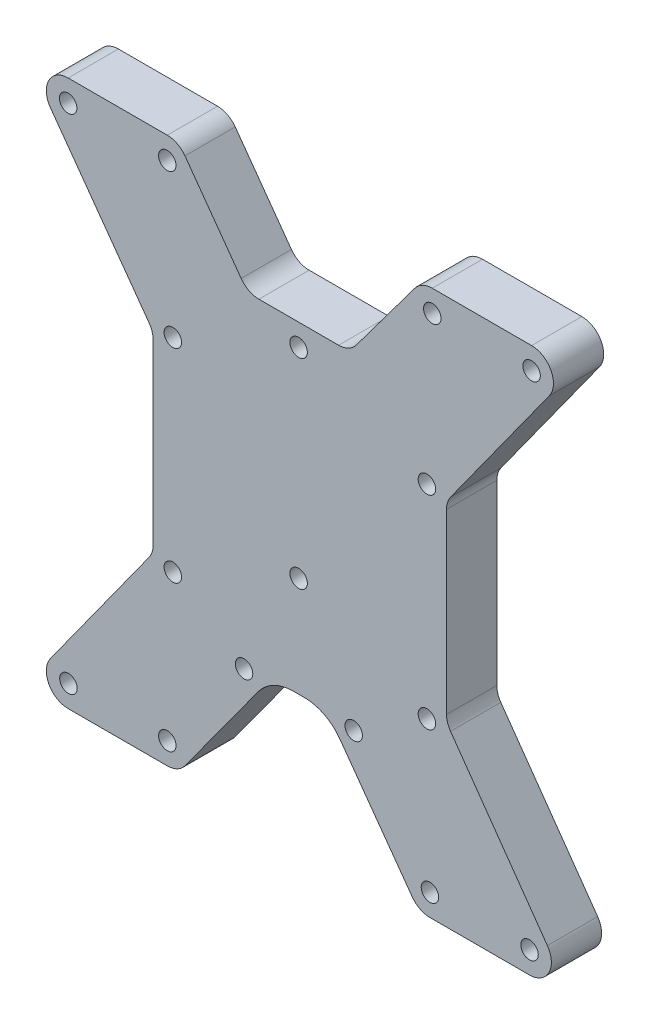
SolidWorks part; units mm, degrees
ref_plane "Plan de face" through (0, 0, 0) normal (0, 0, 1) x (1, 0, 0)
ref_plane "Plan de dessus" through (0, 0, 0) normal (0, 1, 0) x (1, 0, 0)
ref_plane "Plan de droite" through (0, 0, 0) normal (1, 0, 0) x (0, 0, -1)
sketch "Esquisse1" plane through (0, 0, 0) normal (0, 0, 1) x (1, 0, 0)
  line L0 (-12.6183, 25.9) -> (12.606, 25.9) construction
  line L1 (2.6542, -10.0179) -> (-2.3118, -10.0179) construction
  line L2 (-2.3118, -13.0179) -> (2.6542, -13.0179) construction
  line L3 (71.2362, -71.4917) -> (71.2362, -68.4917) construction
  line L4 (71.2362, -68.4917) -> (71.0999, -68.4917) construction
  line L5 (47.9633, -56.5842) -> (29.32, -30.6907) construction
  line L6 (27.3195, -5.7) -> (23.1096, -5.7) construction
  line L7 (18.8849, -21.3318) -> (52.007, -67.3347) construction
  line L8 (60.1223, -71.4917) -> (71.2362, -71.4917) construction
  line L9 (-68.1498, -68.4917) -> (-68.1498, -71.4917) construction
  line L10 (-68.1498, -71.4917) -> (-60.0941, -71.4917) construction
  line L11 (-52.005, -67.371) -> (-18.49, -21.2592) construction
  line L12 (-21.9672, -5.7) -> (-26.9167, -5.7) construction
  line L13 (-29.4418, -31.2247) -> (-48.3355, -57.2197) construction
  line L14 (98.6952, -68.4917) -> (98.6952, -71.4917) construction
  line L15 (98.6952, -71.4917) -> (105.6952, -71.4917) construction
  line L16 (113.8635, -55.7229) -> (69.5522, 7.02) construction
  line L17 (67.7205, 12.7887) -> (67.7205, 94.1277) construction
  line L18 (69.606, 99.9718) -> (114.7511, 162.6551) construction
  line L19 (106.6366, 178.4993) -> (61.18, 178.4993) construction
  line L20 (53.163, 174.4765) -> (26.3399, 138.4997) construction
  line L21 (18.3228, 134.4769) -> (-18.175, 134.4769) construction
  line L22 (-26.2904, 138.6339) -> (-52.007, 174.3514) construction
  line L23 (-60.1223, 178.5083) -> (-105.4777, 178.5083) construction
  line L24 (-113.593, 162.6653) -> (-68.4542, 99.9725) construction
  line L25 (-66.5695, 94.1294) -> (-66.5695, 12.8643) construction
  line L26 (-68.455, 7.0202) -> (-113.5889, -55.6475) construction
  line L27 (-105.4743, -71.4917) -> (-94.6802, -71.4917) construction
  line L28 (-94.6802, -71.4917) -> (-94.6802, -68.4917) construction
  line L29 (-105.1589, -49.0759) -> (-70.1128, -0.415) construction
  line L30 (-63.5695, 17.9568) -> (-63.5695, 86.3085) construction
  line L31 (-70.1128, 107.4104) -> (-106.4556, 157.8865) construction
  line L32 (-96.3999, 175.5083) -> (-68.5391, 175.5083) construction
  line L33 (-48.9794, 165.0121) -> (-28.725, 136.8809) construction
  line L34 (-18.175, 131.4769) -> (-11.549, 131.4769) construction
  line L35 (12.606, 131.4769) -> (18.3228, 131.4769) construction
  line L36 (28.745, 136.7065) -> (50.4923, 165.8754) construction
  line L37 (71.6057, 175.4993) -> (97.7853, 175.4993) construction
  line L38 (106.9929, 157.0163) -> (70.7099, 106.6379) construction
  line L39 (64.7205, 86.3085) -> (64.7205, 17.9568) construction
  line L40 (71.0999, -0.372) -> (107.7809, -52.3106) construction
  line L41 (-12.6183, 25.9) -> (12.606, 25.9)
  line L42 (2.6542, -10.0179) -> (-2.3118, -10.0179)
  line L43 (-2.3118, -13.0179) -> (2.6542, -13.0179)
  line L44 (71.2362, -71.4917) -> (71.2362, -68.4917)
  line L45 (71.2362, -68.4917) -> (71.0999, -68.4917)
  line L46 (47.9633, -56.5842) -> (29.32, -30.6907)
  line L47 (27.3195, -5.7) -> (23.1096, -5.7)
  line L48 (18.8849, -21.3318) -> (52.007, -67.3347)
  line L49 (60.1223, -71.4917) -> (71.2362, -71.4917)
  line L50 (-68.1498, -68.4917) -> (-68.1498, -71.4917)
  line L51 (-68.1498, -71.4917) -> (-60.0941, -71.4917)
  line L52 (-52.005, -67.371) -> (-18.49, -21.2592)
  line L53 (-21.9672, -5.7) -> (-26.9167, -5.7)
  line L54 (-29.4418, -31.2247) -> (-48.3355, -57.2197)
  line L55 (98.6952, -68.4917) -> (98.6952, -71.4917)
  line L56 (98.6952, -71.4917) -> (105.6952, -71.4917)
  line L57 (113.8635, -55.7229) -> (69.5522, 7.02)
  line L58 (67.7205, 12.7887) -> (67.7205, 94.1277)
  line L59 (69.606, 99.9718) -> (114.7511, 162.6551)
  line L60 (106.6366, 178.4993) -> (61.18, 178.4993)
  line L61 (53.163, 174.4765) -> (26.3399, 138.4997)
  line L62 (18.3228, 134.4769) -> (-18.175, 134.4769)
  line L63 (-26.2904, 138.6339) -> (-52.007, 174.3514)
  line L64 (-60.1223, 178.5083) -> (-105.4777, 178.5083)
  line L65 (-113.593, 162.6653) -> (-68.4542, 99.9725)
  line L66 (-66.5695, 94.1294) -> (-66.5695, 12.8643)
  line L67 (-68.455, 7.0202) -> (-113.5889, -55.6475)
  line L68 (-105.4743, -71.4917) -> (-94.6802, -71.4917)
  line L69 (-94.6802, -71.4917) -> (-94.6802, -68.4917)
  line L70 (-105.1589, -49.0759) -> (-70.1128, -0.415)
  line L71 (-63.5695, 17.9568) -> (-63.5695, 86.3085)
  line L72 (-70.1128, 107.4104) -> (-106.4556, 157.8865)
  line L73 (-96.3999, 175.5083) -> (-68.5391, 175.5083)
  line L74 (-48.9794, 165.0121) -> (-28.725, 136.8809)
  line L75 (-18.175, 131.4769) -> (-11.549, 131.4769)
  line L76 (12.606, 131.4769) -> (18.3228, 131.4769)
  line L77 (28.745, 136.7065) -> (50.4923, 165.8754)
  line L78 (71.6057, 175.4993) -> (97.7853, 175.4993)
  line L79 (106.9929, 157.0163) -> (70.7099, 106.6379)
  line L80 (64.7205, 86.3085) -> (64.7205, 17.9568)
  line L81 (71.0999, -0.372) -> (107.7809, -52.3106)
  arc A0 (6.0744, 36.3788) -> (-6.0744, 36.3788) centre (0, 32.9) ccw construction
  arc A1 (-12.6183, 25.9) -> (-6.0744, 36.3788) centre (-25.2791, 41.0893) ccw construction
  arc A2 (6.0744, 36.3788) -> (12.606, 25.9) centre (24.9478, 40.8679) ccw construction
  arc A3 (4.8779, -10.1256) -> (2.6542, -10.0179) centre (2.6542, -33.0179) ccw construction
  arc A4 (-2.3118, -10.0179) -> (-4.3718, -10.1103) centre (-2.3118, -33.0179) ccw construction
  arc A5 (-2.3118, -13.0179) -> (-4.3718, -13.1242) centre (-2.3118, -33.0179) ccw construction
  arc A6 (4.8779, -13.1419) -> (2.6542, -13.0179) centre (2.6542, -33.0179) ccw construction
  arc A7 (67.1223, -61.4917) -> (71.0999, -68.4917) centre (74.4424, -61.9623) ccw construction
  arc A8 (67.1223, -61.4917) -> (56.6448, -55.4166) centre (60.1223, -61.4917) ccw construction
  arc A9 (47.9633, -56.5842) -> (56.6448, -55.4166) centre (50.9426, -45.8776) ccw construction
  arc A10 (32.8466, -20.2301) -> (29.32, -30.6907) centre (46.6577, -30.711) ccw construction
  arc A11 (32.8466, -20.2301) -> (27.3195, -5.7) centre (25.2145, -14.817) ccw construction
  arc A12 (23.1096, -5.7) -> (15.8781, -14.1995) centre (25.2145, -14.817) ccw construction
  arc A13 (15.8781, -14.1995) -> (4.8779, -10.1256) centre (2.6542, -33.0179) ccw construction
  arc A14 (18.8849, -21.3318) -> (4.8779, -13.1419) centre (2.6542, -33.0179) ccw construction
  arc A15 (52.007, -67.3347) -> (60.1223, -71.4917) centre (60.1223, -61.4917) ccw construction
  arc A16 (-60.0941, -71.4917) -> (-52.005, -67.371) centre (-60.0941, -61.4917) ccw construction
  arc A17 (-4.3718, -13.1242) -> (-18.49, -21.2592) centre (-2.3118, -33.0179) ccw construction
  arc A18 (-4.3718, -10.1103) -> (-14.9682, -13.8133) centre (-2.3118, -33.0179) ccw construction
  arc A19 (-14.9682, -13.8133) -> (-21.9672, -5.7) centre (-24.442, -14.9103) ccw construction
  arc A20 (-26.9167, -5.7) -> (-31.9155, -20.8349) centre (-24.442, -14.9103) ccw construction
  arc A21 (-29.4418, -31.2247) -> (-31.9155, -20.8349) centre (-38.3, -27.8444) ccw construction
  arc A22 (-56.0593, -55.7715) -> (-48.3355, -57.2197) centre (-50.5595, -47.7597) ccw construction
  arc A23 (-56.0593, -55.7715) -> (-67.0941, -61.4917) centre (-60.0476, -61.5814) ccw construction
  arc A24 (-68.1498, -68.4917) -> (-67.0941, -61.4917) centre (-74.812, -63.9073) ccw construction
  arc A25 (105.6952, -71.4917) -> (113.8635, -55.7229) centre (105.6952, -61.4917) ccw construction
  arc A26 (67.7205, 12.7887) -> (69.5522, 7.02) centre (77.7205, 12.7887) ccw construction
  arc A27 (69.606, 99.9718) -> (67.7205, 94.1277) centre (77.7205, 94.1277) ccw construction
  arc A28 (114.7511, 162.6551) -> (106.6366, 178.4993) centre (106.6366, 168.4993) ccw construction
  arc A29 (61.18, 178.4993) -> (53.163, 174.4765) centre (61.18, 168.4993) ccw construction
  arc A30 (18.3228, 134.4769) -> (26.3399, 138.4997) centre (18.3228, 144.4769) ccw construction
  arc A31 (-26.2904, 138.6339) -> (-18.175, 134.4769) centre (-18.175, 144.4769) ccw construction
  arc A32 (-52.007, 174.3514) -> (-60.1223, 178.5083) centre (-60.1223, 168.5083) ccw construction
  arc A33 (-105.4777, 178.5083) -> (-113.593, 162.6653) centre (-105.4777, 168.5083) ccw construction
  arc A34 (-66.5695, 94.1294) -> (-68.4542, 99.9725) centre (-76.5695, 94.1294) ccw construction
  arc A35 (-68.455, 7.0202) -> (-66.5695, 12.8643) centre (-76.5695, 12.8643) ccw construction
  arc A36 (-113.5889, -55.6475) -> (-105.4743, -71.4917) centre (-105.4743, -61.4917) ccw construction
  arc A37 (-98.2924, -61.4304) -> (-94.6802, -68.4917) centre (-92.0964, -62.7154) ccw construction
  arc A38 (-98.2924, -61.4304) -> (-101.1294, -55.7715) centre (-105.3547, -61.4304) ccw construction
  arc A39 (-105.1589, -49.0759) -> (-101.1294, -55.7715) centre (-98.5054, -49.6321) ccw construction
  arc A40 (-58.1081, -0.372) -> (-70.1128, -0.415) centre (-64.0027, -30.4536) ccw construction
  arc A41 (-58.1081, -0.372) -> (-54.4317, 12.8646) centre (-57.5695, 6.6073) ccw construction
  arc A42 (-63.5695, 17.9568) -> (-54.4317, 12.8646) centre (-49.0458, 33.2745) ccw construction
  arc A43 (-53.5811, 93.8853) -> (-63.5695, 86.3085) centre (-42.1142, 68.3964) ccw construction
  arc A44 (-53.5811, 93.8853) -> (-56.9135, 106.6071) centre (-57.5695, 99.6379) ccw construction
  arc A45 (-70.1128, 107.4104) -> (-56.9135, 106.6071) centre (-61.4135, 141.5076) ccw construction
  arc A46 (-102.2688, 162.2871) -> (-106.4556, 157.8865) centre (-100.4579, 156.3723) ccw construction
  arc A47 (-102.2688, 162.2871) -> (-98.4777, 168.5083) centre (-105.4777, 168.5083) ccw construction
  arc A48 (-96.3999, 175.5083) -> (-98.4777, 168.5083) centre (-92.0102, 170.397) ccw construction
  arc A49 (-66.9721, 169.9506) -> (-68.5391, 175.5083) centre (-72.0385, 171.5219) ccw construction
  arc A50 (-66.9721, 169.9506) -> (-56.9135, 162.2871) centre (-60.1223, 168.5083) ccw construction
  arc A51 (-48.9794, 165.0121) -> (-56.9135, 162.2871) centre (-50.0685, 155.2701) ccw construction
  arc A52 (-28.725, 136.8809) -> (-18.175, 131.4769) centre (-18.175, 144.4769) ccw construction
  arc A53 (-6.7198, 122.5163) -> (-11.549, 131.4769) centre (-18.5079, 121.9449) ccw construction
  arc A54 (-6.7198, 122.5163) -> (6.7198, 122.5163) centre (0, 124.4769) ccw construction
  arc A55 (12.606, 131.4769) -> (6.7198, 122.5163) centre (15.5638, 123.1203) ccw construction
  arc A56 (18.3228, 131.4769) -> (28.745, 136.7065) centre (18.3228, 144.4769) ccw construction
  arc A57 (56.6448, 163.1671) -> (50.4923, 165.8754) centre (51.3575, 159.4984) ccw construction
  arc A58 (56.6448, 163.1671) -> (68.18, 168.4993) centre (61.18, 168.4993) ccw construction
  arc A59 (71.6057, 175.4993) -> (68.18, 168.4993) centre (75.8723, 169.073) ccw construction
  arc A60 (99.6366, 168.4993) -> (97.7853, 175.4993) centre (92.5359, 170.3662) ccw construction
  arc A61 (99.6366, 168.4993) -> (103.0718, 162.4749) centre (106.6366, 168.4993) ccw construction
  arc A62 (106.9929, 157.0163) -> (103.0718, 162.4749) centre (96.3707, 153.5236) ccw construction
  arc A63 (58.7205, 106.6379) -> (70.7099, 106.6379) centre (64.7152, 127.7009) ccw construction
  arc A64 (58.7205, 106.6379) -> (54.7321, 93.8853) centre (58.7205, 99.6379) ccw construction
  arc A65 (64.7205, 86.3085) -> (54.7321, 93.8853) centre (40.8416, 65.2015) ccw construction
  arc A66 (57.4247, 13.4863) -> (64.7205, 17.9568) centre (56.1884, 23.6927) ccw construction
  arc A67 (57.4247, 13.4863) -> (61.18, 0.0536) centre (58.7205, 6.6073) ccw construction
  arc A68 (71.0999, -0.372) -> (61.18, 0.0536) centre (65.7027, -10.3515) ccw construction
  arc A69 (103.7882, -54.7564) -> (107.7809, -52.3106) centre (101.7834, -47.0019) ccw construction
  arc A70 (103.7882, -54.7564) -> (98.6952, -61.4917) centre (105.4892, -61.3359) ccw construction
  arc A71 (98.6952, -68.4917) -> (98.6952, -61.4917) centre (92.9436, -64.9917) ccw construction
  circle A72 centre (58.7205, 99.6379) radius 2 construction
  circle A73 centre (106.6366, 168.4993) radius 1.8747 construction
  circle A74 centre (61.18, 168.4993) radius 2.1148 construction
  circle A75 centre (-105.4777, 168.5083) radius 1.9743 construction
  circle A76 centre (-60.1223, 168.5083) radius 1.9501 construction
  circle A77 centre (0, 124.4769) radius 2.0764 construction
  circle A78 centre (-57.5695, 99.6379) radius 2.222 construction
  circle A79 centre (0, 32.9) radius 2 construction
  circle A80 centre (58.7205, 6.6073) radius 2 construction
  circle A81 centre (-57.5695, 6.6073) radius 1.906 construction
  circle A82 centre (-105.3547, -61.4304) radius 2 construction
  circle A83 centre (-60.0941, -61.4917) radius 2 construction
  circle A84 centre (60.1223, -61.4917) radius 2 construction
  circle A85 centre (105.6952, -61.4917) radius 2 construction
  circle A86 centre (-24.9792, -15.4385) radius 2 construction
  circle A87 centre (25.2145, -14.817) radius 2 construction
  arc A88 (6.0744, 36.3788) -> (-6.0744, 36.3788) centre (0, 32.9) ccw
  arc A89 (-12.6183, 25.9) -> (-6.0744, 36.3788) centre (-25.2791, 41.0893) ccw
  arc A90 (6.0744, 36.3788) -> (12.606, 25.9) centre (24.9478, 40.8679) ccw
  arc A91 (4.8779, -10.1256) -> (2.6542, -10.0179) centre (2.6542, -33.0179) ccw
  arc A92 (-2.3118, -10.0179) -> (-4.3718, -10.1103) centre (-2.3118, -33.0179) ccw
  arc A93 (-2.3118, -13.0179) -> (-4.3718, -13.1242) centre (-2.3118, -33.0179) ccw
  arc A94 (4.8779, -13.1419) -> (2.6542, -13.0179) centre (2.6542, -33.0179) ccw
  arc A95 (67.1223, -61.4917) -> (71.0999, -68.4917) centre (74.4424, -61.9623) ccw
  arc A96 (67.1223, -61.4917) -> (56.6448, -55.4166) centre (60.1223, -61.4917) ccw
  arc A97 (47.9633, -56.5842) -> (56.6448, -55.4166) centre (50.9426, -45.8776) ccw
  arc A98 (32.8466, -20.2301) -> (29.32, -30.6907) centre (46.6577, -30.711) ccw
  arc A99 (32.8466, -20.2301) -> (27.3195, -5.7) centre (25.2145, -14.817) ccw
  arc A100 (23.1096, -5.7) -> (15.8781, -14.1995) centre (25.2145, -14.817) ccw
  arc A101 (15.8781, -14.1995) -> (4.8779, -10.1256) centre (2.6542, -33.0179) ccw
  arc A102 (18.8849, -21.3318) -> (4.8779, -13.1419) centre (2.6542, -33.0179) ccw
  arc A103 (52.007, -67.3347) -> (60.1223, -71.4917) centre (60.1223, -61.4917) ccw
  arc A104 (-60.0941, -71.4917) -> (-52.005, -67.371) centre (-60.0941, -61.4917) ccw
  arc A105 (-4.3718, -13.1242) -> (-18.49, -21.2592) centre (-2.3118, -33.0179) ccw
  arc A106 (-4.3718, -10.1103) -> (-14.9682, -13.8133) centre (-2.3118, -33.0179) ccw
  arc A107 (-14.9682, -13.8133) -> (-21.9672, -5.7) centre (-24.442, -14.9103) ccw
  arc A108 (-26.9167, -5.7) -> (-31.9155, -20.8349) centre (-24.442, -14.9103) ccw
  arc A109 (-29.4418, -31.2247) -> (-31.9155, -20.8349) centre (-38.3, -27.8444) ccw
  arc A110 (-56.0593, -55.7715) -> (-48.3355, -57.2197) centre (-50.5595, -47.7597) ccw
  arc A111 (-56.0593, -55.7715) -> (-67.0941, -61.4917) centre (-60.0476, -61.5814) ccw
  arc A112 (-68.1498, -68.4917) -> (-67.0941, -61.4917) centre (-74.812, -63.9073) ccw
  arc A113 (105.6952, -71.4917) -> (113.8635, -55.7229) centre (105.6952, -61.4917) ccw
  arc A114 (67.7205, 12.7887) -> (69.5522, 7.02) centre (77.7205, 12.7887) ccw
  arc A115 (69.606, 99.9718) -> (67.7205, 94.1277) centre (77.7205, 94.1277) ccw
  arc A116 (114.7511, 162.6551) -> (106.6366, 178.4993) centre (106.6366, 168.4993) ccw
  arc A117 (61.18, 178.4993) -> (53.163, 174.4765) centre (61.18, 168.4993) ccw
  arc A118 (18.3228, 134.4769) -> (26.3399, 138.4997) centre (18.3228, 144.4769) ccw
  arc A119 (-26.2904, 138.6339) -> (-18.175, 134.4769) centre (-18.175, 144.4769) ccw
  arc A120 (-52.007, 174.3514) -> (-60.1223, 178.5083) centre (-60.1223, 168.5083) ccw
  arc A121 (-105.4777, 178.5083) -> (-113.593, 162.6653) centre (-105.4777, 168.5083) ccw
  arc A122 (-66.5695, 94.1294) -> (-68.4542, 99.9725) centre (-76.5695, 94.1294) ccw
  arc A123 (-68.455, 7.0202) -> (-66.5695, 12.8643) centre (-76.5695, 12.8643) ccw
  arc A124 (-113.5889, -55.6475) -> (-105.4743, -71.4917) centre (-105.4743, -61.4917) ccw
  arc A125 (-98.2924, -61.4304) -> (-94.6802, -68.4917) centre (-92.0964, -62.7154) ccw
  arc A126 (-98.2924, -61.4304) -> (-101.1294, -55.7715) centre (-105.3547, -61.4304) ccw
  arc A127 (-105.1589, -49.0759) -> (-101.1294, -55.7715) centre (-98.5054, -49.6321) ccw
  arc A128 (-58.1081, -0.372) -> (-70.1128, -0.415) centre (-64.0027, -30.4536) ccw
  arc A129 (-58.1081, -0.372) -> (-54.4317, 12.8646) centre (-57.5695, 6.6073) ccw
  arc A130 (-63.5695, 17.9568) -> (-54.4317, 12.8646) centre (-49.0458, 33.2745) ccw
  arc A131 (-53.5811, 93.8853) -> (-63.5695, 86.3085) centre (-42.1142, 68.3964) ccw
  arc A132 (-53.5811, 93.8853) -> (-56.9135, 106.6071) centre (-57.5695, 99.6379) ccw
  arc A133 (-70.1128, 107.4104) -> (-56.9135, 106.6071) centre (-61.4135, 141.5076) ccw
  arc A134 (-102.2688, 162.2871) -> (-106.4556, 157.8865) centre (-100.4579, 156.3723) ccw
  arc A135 (-102.2688, 162.2871) -> (-98.4777, 168.5083) centre (-105.4777, 168.5083) ccw
  arc A136 (-96.3999, 175.5083) -> (-98.4777, 168.5083) centre (-92.0102, 170.397) ccw
  arc A137 (-66.9721, 169.9506) -> (-68.5391, 175.5083) centre (-72.0385, 171.5219) ccw
  arc A138 (-66.9721, 169.9506) -> (-56.9135, 162.2871) centre (-60.1223, 168.5083) ccw
  arc A139 (-48.9794, 165.0121) -> (-56.9135, 162.2871) centre (-50.0685, 155.2701) ccw
  arc A140 (-28.725, 136.8809) -> (-18.175, 131.4769) centre (-18.175, 144.4769) ccw
  arc A141 (-6.7198, 122.5163) -> (-11.549, 131.4769) centre (-18.5079, 121.9449) ccw
  arc A142 (-6.7198, 122.5163) -> (6.7198, 122.5163) centre (0, 124.4769) ccw
  arc A143 (12.606, 131.4769) -> (6.7198, 122.5163) centre (15.5638, 123.1203) ccw
  arc A144 (18.3228, 131.4769) -> (28.745, 136.7065) centre (18.3228, 144.4769) ccw
  arc A145 (56.6448, 163.1671) -> (50.4923, 165.8754) centre (51.3575, 159.4984) ccw
  arc A146 (56.6448, 163.1671) -> (68.18, 168.4993) centre (61.18, 168.4993) ccw
  arc A147 (71.6057, 175.4993) -> (68.18, 168.4993) centre (75.8723, 169.073) ccw
  arc A148 (99.6366, 168.4993) -> (97.7853, 175.4993) centre (92.5359, 170.3662) ccw
  arc A149 (99.6366, 168.4993) -> (103.0718, 162.4749) centre (106.6366, 168.4993) ccw
  arc A150 (106.9929, 157.0163) -> (103.0718, 162.4749) centre (96.3707, 153.5236) ccw
  arc A151 (58.7205, 106.6379) -> (70.7099, 106.6379) centre (64.7152, 127.7009) ccw
  arc A152 (58.7205, 106.6379) -> (54.7321, 93.8853) centre (58.7205, 99.6379) ccw
  arc A153 (64.7205, 86.3085) -> (54.7321, 93.8853) centre (40.8416, 65.2015) ccw
  arc A154 (57.4247, 13.4863) -> (64.7205, 17.9568) centre (56.1884, 23.6927) ccw
  arc A155 (57.4247, 13.4863) -> (61.18, 0.0536) centre (58.7205, 6.6073) ccw
  arc A156 (71.0999, -0.372) -> (61.18, 0.0536) centre (65.7027, -10.3515) ccw
  arc A157 (103.7882, -54.7564) -> (107.7809, -52.3106) centre (101.7834, -47.0019) ccw
  arc A158 (103.7882, -54.7564) -> (98.6952, -61.4917) centre (105.4892, -61.3359) ccw
  arc A159 (98.6952, -68.4917) -> (98.6952, -61.4917) centre (92.9436, -64.9917) ccw
  circle A160 centre (58.7205, 99.6379) radius 2
  circle A161 centre (106.6366, 168.4993) radius 1.8747
  circle A162 centre (61.18, 168.4993) radius 2.1148
  circle A163 centre (-105.4777, 168.5083) radius 1.9743
  circle A164 centre (-60.1223, 168.5083) radius 1.9501
  circle A165 centre (0, 124.4769) radius 2.0764
  circle A166 centre (-57.5695, 99.6379) radius 2.222
  circle A167 centre (0, 32.9) radius 2
  circle A168 centre (58.7205, 6.6073) radius 2
  circle A169 centre (-57.5695, 6.6073) radius 1.906
  circle A170 centre (-105.3547, -61.4304) radius 2
  circle A171 centre (-60.0941, -61.4917) radius 2
  circle A172 centre (60.1223, -61.4917) radius 2
  circle A173 centre (105.6952, -61.4917) radius 2
  circle A174 centre (-24.9792, -15.4385) radius 2
  circle A175 centre (25.2145, -14.817) radius 2
extrude "Boss.-Extru.1" add sketch "Esquisse1" along normal blind 20
sketch "Esquisse2" plane through (0, 0, 20) normal (0, 0, 1) x (1, 0, 0)
  line L0 (-113.593, 162.6653) -> (-68.4542, 99.9725) construction
  line L1 (-66.5695, 94.1294) -> (-66.5695, 12.8643) construction
  line L2 (-68.455, 7.0202) -> (-113.5889, -55.6475) construction
  line L3 (-105.4743, -71.4917) -> (-94.6802, -71.4917) construction
  line L4 (-94.6802, -71.4917) -> (-68.1498, -71.4917) construction
  line L5 (-68.1498, -71.4917) -> (-60.0941, -71.4917) construction
  line L6 (-52.005, -67.371) -> (-18.49, -21.2592) construction
  line L7 (-2.3118, -13.0179) -> (2.6542, -13.0179) construction
  line L8 (18.8849, -21.3318) -> (52.007, -67.3347) construction
  line L9 (60.1223, -71.4917) -> (71.2362, -71.4917) construction
  line L10 (98.6952, -71.4917) -> (105.6952, -71.4917) construction
  line L11 (71.2362, -71.4917) -> (98.6952, -71.4917) construction
  line L12 (113.8635, -55.7229) -> (69.5522, 7.02) construction
  line L13 (67.7205, 12.7887) -> (67.7205, 94.1277) construction
  line L14 (69.606, 99.9718) -> (114.7511, 162.6551) construction
  line L15 (106.6366, 178.4993) -> (61.18, 178.4993) construction
  line L16 (53.163, 174.4765) -> (26.3399, 138.4997) construction
  line L17 (18.3228, 134.4769) -> (-18.175, 134.4769) construction
  line L18 (-26.2904, 138.6339) -> (-52.007, 174.3514) construction
  line L19 (-60.1223, 178.5083) -> (-105.4777, 178.5083) construction
  line L20 (-113.593, 162.6653) -> (-68.4542, 99.9725)
  line L21 (-66.5695, 94.1294) -> (-66.5695, 12.8643)
  line L22 (-68.455, 7.0202) -> (-113.5889, -55.6475)
  line L23 (-105.4743, -71.4917) -> (-94.6802, -71.4917)
  line L24 (-94.6802, -71.4917) -> (-68.1498, -71.4917)
  line L25 (-68.1498, -71.4917) -> (-60.0941, -71.4917)
  line L26 (-52.005, -67.371) -> (-18.49, -21.2592)
  line L27 (-2.3118, -13.0179) -> (2.6542, -13.0179)
  line L28 (18.8849, -21.3318) -> (52.007, -67.3347)
  line L29 (60.1223, -71.4917) -> (71.2362, -71.4917)
  line L30 (98.6952, -71.4917) -> (105.6952, -71.4917)
  line L31 (71.2362, -71.4917) -> (98.6952, -71.4917)
  line L32 (113.8635, -55.7229) -> (69.5522, 7.02)
  line L33 (67.7205, 12.7887) -> (67.7205, 94.1277)
  line L34 (69.606, 99.9718) -> (114.7511, 162.6551)
  line L35 (106.6366, 178.4993) -> (61.18, 178.4993)
  line L36 (53.163, 174.4765) -> (26.3399, 138.4997)
  line L37 (18.3228, 134.4769) -> (-18.175, 134.4769)
  line L38 (-26.2904, 138.6339) -> (-52.007, 174.3514)
  line L39 (-60.1223, 178.5083) -> (-105.4777, 178.5083)
  arc A0 (-66.5695, 94.1294) -> (-68.4542, 99.9725) centre (-76.5695, 94.1294) ccw construction
  arc A1 (-68.455, 7.0202) -> (-66.5695, 12.8643) centre (-76.5695, 12.8643) ccw construction
  arc A2 (-113.5889, -55.6475) -> (-105.4743, -71.4917) centre (-105.4743, -61.4917) ccw construction
  arc A3 (-60.0941, -71.4917) -> (-52.005, -67.371) centre (-60.0941, -61.4917) ccw construction
  arc A4 (-2.3118, -13.0179) -> (-18.49, -21.2592) centre (-2.3118, -33.0179) ccw construction
  arc A5 (18.8849, -21.3318) -> (2.6542, -13.0179) centre (2.6542, -33.0179) ccw construction
  arc A6 (52.007, -67.3347) -> (60.1223, -71.4917) centre (60.1223, -61.4917) ccw construction
  arc A7 (105.6952, -71.4917) -> (113.8635, -55.7229) centre (105.6952, -61.4917) ccw construction
  arc A8 (67.7205, 12.7887) -> (69.5522, 7.02) centre (77.7205, 12.7887) ccw construction
  arc A9 (69.606, 99.9718) -> (67.7205, 94.1277) centre (77.7205, 94.1277) ccw construction
  arc A10 (114.7511, 162.6551) -> (106.6366, 178.4993) centre (106.6366, 168.4993) ccw construction
  arc A11 (61.18, 178.4993) -> (53.163, 174.4765) centre (61.18, 168.4993) ccw construction
  arc A12 (18.3228, 134.4769) -> (26.3399, 138.4997) centre (18.3228, 144.4769) ccw construction
  arc A13 (-26.2904, 138.6339) -> (-18.175, 134.4769) centre (-18.175, 144.4769) ccw construction
  arc A14 (-52.007, 174.3514) -> (-60.1223, 178.5083) centre (-60.1223, 168.5083) ccw construction
  arc A15 (-105.4777, 178.5083) -> (-113.593, 162.6653) centre (-105.4777, 168.5083) ccw construction
  arc A16 (-66.5695, 94.1294) -> (-68.4542, 99.9725) centre (-76.5695, 94.1294) ccw
  arc A17 (-68.455, 7.0202) -> (-66.5695, 12.8643) centre (-76.5695, 12.8643) ccw
  arc A18 (-113.5889, -55.6475) -> (-105.4743, -71.4917) centre (-105.4743, -61.4917) ccw
  arc A19 (-60.0941, -71.4917) -> (-52.005, -67.371) centre (-60.0941, -61.4917) ccw
  arc A20 (-2.3118, -13.0179) -> (-18.49, -21.2592) centre (-2.3118, -33.0179) ccw
  arc A21 (18.8849, -21.3318) -> (2.6542, -13.0179) centre (2.6542, -33.0179) ccw
  arc A22 (52.007, -67.3347) -> (60.1223, -71.4917) centre (60.1223, -61.4917) ccw
  arc A23 (105.6952, -71.4917) -> (113.8635, -55.7229) centre (105.6952, -61.4917) ccw
  arc A24 (67.7205, 12.7887) -> (69.5522, 7.02) centre (77.7205, 12.7887) ccw
  arc A25 (69.606, 99.9718) -> (67.7205, 94.1277) centre (77.7205, 94.1277) ccw
  arc A26 (114.7511, 162.6551) -> (106.6366, 178.4993) centre (106.6366, 168.4993) ccw
  arc A27 (61.18, 178.4993) -> (53.163, 174.4765) centre (61.18, 168.4993) ccw
  arc A28 (18.3228, 134.4769) -> (26.3399, 138.4997) centre (18.3228, 144.4769) ccw
  arc A29 (-26.2904, 138.6339) -> (-18.175, 134.4769) centre (-18.175, 144.4769) ccw
  arc A30 (-52.007, 174.3514) -> (-60.1223, 178.5083) centre (-60.1223, 168.5083) ccw
  arc A31 (-105.4777, 178.5083) -> (-113.593, 162.6653) centre (-105.4777, 168.5083) ccw
extrude "Boss.-Extru.2" add sketch "Esquisse2" along normal blind 3
sketch "Esquisse3" plane through (0, 0, 23) normal (0, 0, 1) x (1, 0, 0)
  circle A0 centre (58.7205, 99.6379) radius 2 construction
  circle A1 centre (-105.3547, -61.4304) radius 2 construction
  circle A2 centre (-60.0941, -61.4917) radius 2 construction
  circle A3 centre (105.6952, -61.4917) radius 2 construction
  circle A4 centre (60.1223, -61.4917) radius 2 construction
  circle A5 centre (25.2145, -14.817) radius 2 construction
  circle A6 centre (-24.9792, -15.4385) radius 2 construction
  circle A7 centre (-57.5695, 6.6073) radius 1.906 construction
  circle A8 centre (0, 32.9) radius 2 construction
  circle A9 centre (58.7205, 6.6073) radius 2 construction
  circle A10 centre (106.6366, 168.4993) radius 1.8747 construction
  circle A11 centre (61.18, 168.4993) radius 2.1148 construction
  circle A12 centre (0, 124.4769) radius 2.0764 construction
  circle A13 centre (-57.5695, 99.6379) radius 2.222 construction
  circle A14 centre (-60.1223, 168.5083) radius 1.9501 construction
  circle A15 centre (-105.4777, 168.5083) radius 1.9743 construction
  circle A16 centre (58.7205, 99.6379) radius 2
  circle A17 centre (-105.3547, -61.4304) radius 2
  circle A18 centre (-60.0941, -61.4917) radius 2
  circle A19 centre (105.6952, -61.4917) radius 2
  circle A20 centre (60.1223, -61.4917) radius 2
  circle A21 centre (25.2145, -14.817) radius 2
  circle A22 centre (-24.9792, -15.4385) radius 2
  circle A23 centre (-57.5695, 6.6073) radius 1.906
  circle A24 centre (0, 32.9) radius 2
  circle A25 centre (58.7205, 6.6073) radius 2
  circle A26 centre (106.6366, 168.4993) radius 1.8747
  circle A27 centre (61.18, 168.4993) radius 2.1148
  circle A28 centre (0, 124.4769) radius 2.0764
  circle A29 centre (-57.5695, 99.6379) radius 2.222
  circle A30 centre (-60.1223, 168.5083) radius 1.9501
  circle A31 centre (-105.4777, 168.5083) radius 1.9743
extrude "Enlèv. mat.-Extru.1" cut sketch "Esquisse3" against normal blind 3
sketch "Esquisse5" plane through (0, 0, 23) normal (0, 0, 1) x (1, 0, 0)
  circle A0 centre (-105.4777, 168.5083) radius 4
  circle A1 centre (-60.1223, 168.5083) radius 4
  circle A2 centre (0, 124.4769) radius 4
  circle A3 centre (-57.5695, 99.6379) radius 4
  circle A4 centre (61.18, 168.4993) radius 4
  circle A5 centre (106.6366, 168.4993) radius 4
  circle A6 centre (58.7205, 99.6379) radius 4
  circle A7 centre (0, 32.9) radius 4
  circle A8 centre (-57.5695, 6.6073) radius 4
  circle A9 centre (58.7205, 6.6073) radius 4
  circle A10 centre (-24.9792, -15.4385) radius 4
  circle A11 centre (25.2145, -14.817) radius 4
  circle A12 centre (60.1223, -61.4917) radius 4
  circle A13 centre (105.6952, -61.4917) radius 4
  circle A14 centre (-60.0941, -61.4917) radius 4
  circle A15 centre (-105.3547, -61.4304) radius 4
  dimension "D1" = 8
  dimension "D2" = 8
  dimension "D3" = 8
  dimension "D4" = 8
  dimension "D5" = 8
  dimension "D6" = 8
  dimension "D7" = 8
  dimension "D8" = 8
  dimension "D9" = 8
  dimension "D10" = 8
  dimension "D11" = 8
  dimension "D12" = 8
  dimension "D13" = 8
  dimension "D14" = 8
  dimension "D15" = 8
  dimension "D16" = 8
extrude "Enlèv. mat.-Extru.2" cut sketch "Esquisse5" against normal blind 15
sketch "Esquisse6" plane through (0, 0, 20) normal (0, 0, -1) x (-1, 0, 0)
  arc A0 (-6.7198, 122.5163) -> (-6.0744, 36.3788) centre (-254.5926, 77.5878) cw
  arc A3 (6.7198, 122.5163) -> (6.0744, 36.3788) centre (256.5692, 77.573) ccw
  arc A4 (-6.0744, 36.3788) -> (6.0744, 36.3788) centre (0, 32.9) cw
  arc A5 (-6.7198, 122.5163) -> (6.7198, 122.5163) centre (0, 124.4769) ccw
  arc A10 (20.91, -7.0506) -> (54.4317, 12.8646) centre (65.1618, -43.3664) cw
  arc A12 (54.4317, 12.8646) -> (58.1081, -0.372) centre (57.5695, 6.6073) ccw construction
  arc A13 (54.4317, 12.8646) -> (57.5695, -0.3927) centre (57.5695, 6.6073) ccw
  arc A15 (-54.7477, 12.1044) -> (-23.1096, -5.7) centre (-87.4531, -83.025) cw
  arc A17 (-54.7477, 12.1044) -> (-58.9836, 0) centre (-59.5161, 6.9797) cw
  arc A18 (-32.9223, -19.221) -> (-23.1096, -5.7) centre (-22.7039, -16.3157) cw
  arc A19 (-58.9836, 0) -> (-32.9223, -19.221) centre (-73.7835, -47.3453) cw
  arc A20 (33.8131, -16.6816) -> (57.5695, -0.3927) centre (66.457, -38.8228) cw
  arc A21 (31.9155, -20.8349) -> (26.9167, -5.7) centre (24.442, -14.9103) ccw construction
  arc A22 (20.91, -7.0506) -> (33.8131, -16.6816) centre (24.3031, -15.9636) cw
extrude "Boss.-Extru.6" add sketch "Esquisse6" along normal blind 10
